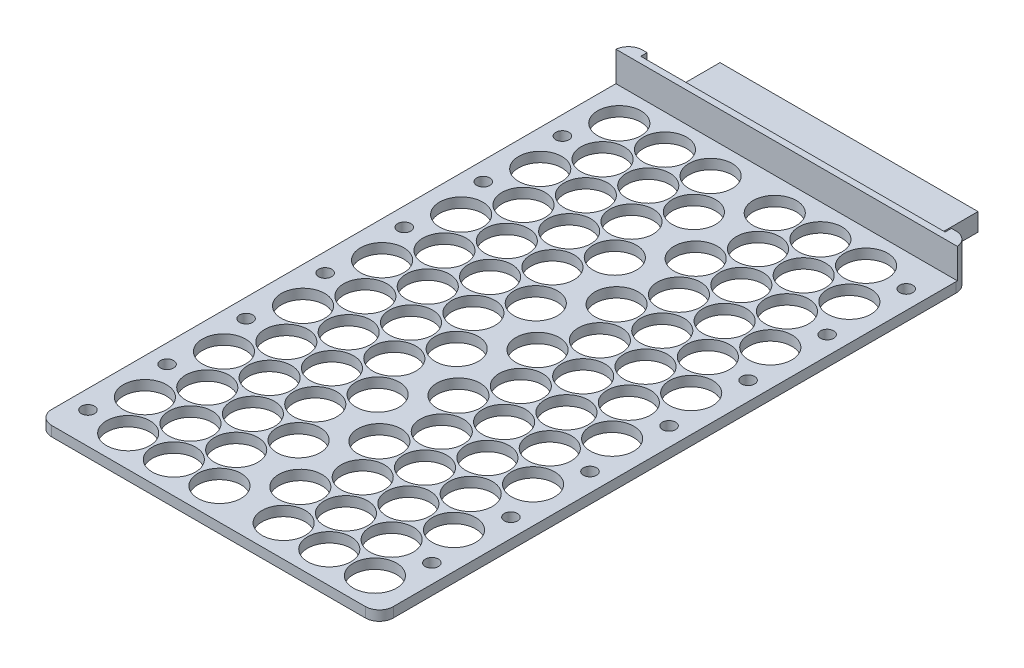
SolidWorks part; units mm, degrees
ref_plane "Front Plane" through (0, 0, 0) normal (0, 0, 1) x (1, 0, 0)
ref_plane "Top Plane" through (0, 0, 0) normal (0, 1, 0) x (1, 0, 0)
ref_plane "Right Plane" through (0, 0, 0) normal (1, 0, 0) x (0, 0, -1)
sketch "Sketch2" plane through (0, 0, 0) normal (0, 1, 0) x (1, 0, 0)
  line L1 (0, 0) -> (171.7, 0)
  line L2 (0, 0) -> (0, 290.6287)
  line L3 (0, 290.6287) -> (171.7, 290.6287)
  line L4 (171.7, 0) -> (171.7, 290.6287)
  dimension "D1" = 171.7
  dimension "D2" = 290.6287
extrude "Boss-Extrude6" add sketch "Sketch2" along normal blind 5
sketch "Sketch1" plane through (0, 0, 0) normal (0, 1, 0) x (1, 0, 0)
  line L1 (0, 0) -> (171.7029, 0)
  line L2 (0, 0) -> (0, 290.6287)
  line L3 (0, 290.6287) -> (171.7029, 290.6287)
  line L4 (171.7029, 0) -> (171.7029, 290.6287)
  line L5 (29.5647, 15.875) -> (18.0897, 35.7503) construction
  line L6 (18.0897, 35.7503) -> (18.0897, 15.875) construction
  line L7 (18.0897, 15.875) -> (29.5647, 15.875) construction
  line L8 (29.5647, 55.6256) -> (18.0897, 35.7503) construction
  line L9 (18.0897, 35.7503) -> (29.5647, 35.7503) construction
  line L10 (29.5647, 35.7503) -> (29.5647, 55.6256) construction
  line L11 (29.5647, 55.6256) -> (0, 55.6256) construction
  line L12 (0, 55.6256) -> (18.0897, 75.5008) construction
  line L13 (142.1382, 35.7503) -> (171.7029, 35.7503) construction
  line L14 (171.7029, 35.7503) -> (153.6132, 15.875) construction
  circle A1 centre (29.5647, 15.875) radius 10.875
  circle A2 centre (18.0897, 35.7503) radius 10.875
  circle A3 centre (41.0397, 35.7503) radius 10.875
  circle A4 centre (52.5147, 15.875) radius 10.875
  circle A5 centre (63.9897, 35.7503) radius 10.875
  circle A6 centre (75.4647, 15.875) radius 10.875
  circle A43 centre (96.2382, 35.7503) radius 10.875
  circle A44 centre (119.1882, 35.7503) radius 10.875
  circle A45 centre (142.1382, 35.7503) radius 10.875
  circle A46 centre (153.6132, 15.875) radius 10.875
  circle A47 centre (130.6632, 15.875) radius 10.875
  circle A48 centre (107.7132, 15.875) radius 10.875
  circle A49 centre (96.2382, 75.5008) radius 10.875
  circle A50 centre (119.1882, 75.5008) radius 10.875
  circle A51 centre (142.1382, 75.5008) radius 10.875
  circle A52 centre (153.6132, 55.6256) radius 10.875
  circle A53 centre (130.6632, 55.6256) radius 10.875
  circle A54 centre (107.7132, 55.6256) radius 10.875
  circle A55 centre (96.2382, 115.2514) radius 10.875
  circle A56 centre (119.1882, 115.2514) radius 10.875
  circle A57 centre (142.1382, 115.2514) radius 10.875
  circle A58 centre (153.6132, 95.3761) radius 10.875
  circle A59 centre (130.6632, 95.3761) radius 10.875
  circle A60 centre (107.7132, 95.3761) radius 10.875
  circle A61 centre (96.2382, 155.002) radius 10.875
  circle A62 centre (119.1882, 155.002) radius 10.875
  circle A63 centre (142.1382, 155.002) radius 10.875
  circle A64 centre (153.6132, 135.1267) radius 10.875
  circle A65 centre (130.6632, 135.1267) radius 10.875
  circle A66 centre (107.7132, 135.1267) radius 10.875
  circle A67 centre (96.2382, 194.7525) radius 10.875
  circle A68 centre (119.1882, 194.7525) radius 10.875
  circle A69 centre (142.1382, 194.7525) radius 10.875
  circle A70 centre (153.6132, 174.8773) radius 10.875
  circle A71 centre (130.6632, 174.8773) radius 10.875
  circle A72 centre (107.7132, 174.8773) radius 10.875
  circle A73 centre (96.2382, 234.5031) radius 10.875
  circle A74 centre (119.1882, 234.5031) radius 10.875
  circle A75 centre (142.1382, 234.5031) radius 10.875
  circle A76 centre (153.6132, 214.6278) radius 10.875
  circle A77 centre (130.6632, 214.6278) radius 10.875
  circle A78 centre (107.7132, 214.6278) radius 10.875
  circle A79 centre (96.2382, 274.2537) radius 10.875
  circle A80 centre (119.1882, 274.2537) radius 10.875
  circle A81 centre (142.1382, 274.2537) radius 10.875
  circle A82 centre (153.6132, 254.3784) radius 10.875
  circle A83 centre (130.6632, 254.3784) radius 10.875
  circle A84 centre (107.7132, 254.3784) radius 10.875
  circle A127 centre (18.0897, 75.5008) radius 10.875
  circle A128 centre (41.0397, 75.5008) radius 10.875
  circle A129 centre (63.9897, 75.5008) radius 10.875
  circle A130 centre (75.4647, 55.6256) radius 10.875
  circle A131 centre (52.5147, 55.6256) radius 10.875
  circle A132 centre (29.5647, 55.6256) radius 10.875
  circle A133 centre (18.0897, 115.2514) radius 10.875
  circle A134 centre (41.0397, 115.2514) radius 10.875
  circle A135 centre (63.9897, 115.2514) radius 10.875
  circle A136 centre (75.4647, 95.3761) radius 10.875
  circle A137 centre (52.5147, 95.3761) radius 10.875
  circle A138 centre (29.5647, 95.3761) radius 10.875
  circle A139 centre (18.0897, 155.002) radius 10.875
  circle A140 centre (41.0397, 155.002) radius 10.875
  circle A141 centre (63.9897, 155.002) radius 10.875
  circle A142 centre (75.4647, 135.1267) radius 10.875
  circle A143 centre (52.5147, 135.1267) radius 10.875
  circle A144 centre (29.5647, 135.1267) radius 10.875
  circle A145 centre (18.0897, 194.7525) radius 10.875
  circle A146 centre (41.0397, 194.7525) radius 10.875
  circle A147 centre (63.9897, 194.7525) radius 10.875
  circle A148 centre (75.4647, 174.8773) radius 10.875
  circle A149 centre (52.5147, 174.8773) radius 10.875
  circle A150 centre (29.5647, 174.8773) radius 10.875
  circle A151 centre (18.0897, 234.5031) radius 10.875
  circle A152 centre (41.0397, 234.5031) radius 10.875
  circle A153 centre (63.9897, 234.5031) radius 10.875
  circle A154 centre (75.4647, 214.6278) radius 10.875
  circle A155 centre (52.5147, 214.6278) radius 10.875
  circle A156 centre (29.5647, 214.6278) radius 10.875
  circle A157 centre (18.0897, 274.2537) radius 10.875
  circle A158 centre (41.0397, 274.2537) radius 10.875
  circle A159 centre (63.9897, 274.2537) radius 10.875
  circle A160 centre (75.4647, 254.3784) radius 10.875
  circle A161 centre (52.5147, 254.3784) radius 10.875
  circle A162 centre (29.5647, 254.3784) radius 10.875
  point P10 (0, 0)
  dimension "D1" = 21.75
  dimension "D2" = 15.875
  dimension "D3" = 22.95
  dimension "D5" = 60
  dimension "D8" = 22.95
  dimension "D9" = 22.95
  dimension "D10" = 60
  dimension "D13" = 28.75
  dimension "D4" = 16.375
  dimension "D16" = 26.875
  dimension "D14" = 26.875
  dimension "D6" = 3
  dimension "D7" = 1
  dimension "D11" = 2
  dimension "D12" = 7
extrude "Cut-Extrude1" cut sketch "Sketch1" along normal blind 7 contours A47 | A46 | A45 | A44 | A43 | A54 | A53 | A52 | A51 | A50 | A49 | A60 | A59 | A58 | A57 | A56 | A55 | A66 | A65 | A64 | A63 | A62 | A61 | A72 | A67 | A78 | A73 | A84 | A79 | A80 | A81 | A82 | A83 | A74 | A75 | A77 | A76 | A69 | A70 | A71 | A68 | A159 | A158 | A157 | A162 | A161 | A160 | A153 | A152 | A156 | A151 | A155 | A154 | A147 | A146 | A145 | A148 | A141 | A149 | A150 | A140 | A142 | A143 | A144 | A139 | A133 | A134 | A135 | A136 | A137 | A138 | A128 | A127 | A129 | A130 | A131 | A132 | A2 | A3 | A5 | A6 | A4 | A1 | A48
sketch "Sketch5" plane through (0, 5, 0) normal (0, 1, 0) x (1, 0, 0)
  line L0 (9.3449, 254.3784) -> (18.0897, 274.2537) construction
  line L1 (9.3449, 254.3784) -> (0, 254.3784) construction
  line L2 (18.0897, 234.5031) -> (9.3449, 254.3784) construction
  line L3 (18.6897, 254.3784) -> (9.3449, 254.3784) construction
  line L4 (142.1382, 75.5008) -> (162.3566, 75.5008) construction
  line L5 (0, 290.6287) -> (0, 0) construction
  line L6 (162.3566, 35.7503) -> (171.7, 35.7503) construction
  line L7 (153.6132, 15.875) -> (162.3566, 35.7503) construction
  line L8 (162.3566, 35.7503) -> (153.6132, 55.6256) construction
  line L9 (171.7, 0) -> (171.7, 290.6287) construction
  line L10 (162.3566, 35.7503) -> (153.0132, 35.7503) construction
  line L12 (29.5647, 214.6278) -> (9.3449, 214.6278) construction
  circle A1 centre (9.3449, 254.3784) radius 3.3
  circle A4 centre (162.3566, 35.7503) radius 3.3
  circle A7 centre (162.3566, 75.5008) radius 3.3
  circle A8 centre (162.3566, 115.2514) radius 3.3
  circle A9 centre (162.3566, 155.002) radius 3.3
  circle A10 centre (162.3566, 194.7525) radius 3.3
  circle A11 centre (162.3566, 234.5031) radius 3.3
  circle A12 centre (162.3566, 274.2537) radius 3.3
  circle A15 centre (9.3449, 214.6278) radius 3.3
  circle A16 centre (9.3449, 174.8773) radius 3.3
  circle A17 centre (9.3449, 135.1267) radius 3.3
  circle A18 centre (9.3449, 95.3761) radius 3.3
  circle A19 centre (9.3449, 55.6256) radius 3.3
  circle A20 centre (9.3449, 15.875) radius 3.3
  circle A21 centre (29.5647, 254.3784) radius 10.875 construction
  circle A22 centre (142.1382, 35.7503) radius 10.875 construction
  dimension "D1" = 6.6
  dimension "D2" = 6.6
  dimension "D3" = 7
  dimension "D4" = 7
extrude "Cut-Extrude3" cut sketch "Sketch5" against normal up to surface (5 mm away) up to face at (96.2382, 0, -64.6258)
sketch "Sketch12" plane through (0, 0, -290.6287) normal (0, 0, -1) x (-1, 0, 0)
  line L5 (-171.7, 5) -> (0, 5)
  line L6 (-171.7, 5) -> (-171.7, 20)
  line L7 (0, 5) -> (0, 0) construction
  line L8 (-171.7, 0) -> (0, 0)
  line L12 (-171.7, 0) -> (0, 0)
  line L13 (-171.7, 0) -> (-171.7, 5)
  line L15 (0, 0) -> (0, 5)
  line L16 (-171.7, 20) -> (0, 20)
  line L17 (-171.7, 5) -> (0, 5)
  line L26 (-171.7, 5) -> (0, 5) construction
  line L27 (0, 5) -> (0, 20)
  dimension "D1" = 15
extrude "Boss-Extrude9" add sketch "Sketch12" along normal blind 6.35
sketch "Sketch13" plane through (0, 0, -296.9787) normal (0, 0, -1) x (-1, 0, 0)
  line L1 (-162.355, 9) -> (-9.345, 9)
  line L2 (-162.355, 9) -> (-162.355, 20)
  line L3 (-162.355, 20) -> (-9.345, 20)
  line L4 (-9.345, 9) -> (-9.345, 20)
  line L8 (-162.355, 20) -> (-171.7, 20) construction
  line L10 (-171.7, 20) -> (0, 20) construction
  line L11 (-9.345, 20) -> (0, 20) construction
  dimension "D1" = 153.01
  dimension "D2" = 11
extrude "Cut-Extrude7" cut sketch "Sketch13" against normal blind 3.18
sketch "Sketch14" plane through (0, 0, -296.9787) normal (0, 0, -1) x (-1, 0, 0)
  line L6 (-171.7, 20) -> (-171.7, 0) construction
  line L7 (0, 0) -> (0, 20) construction
  line L9 (-150.7, 0) -> (-21, 0)
  line L10 (-150.7, 0) -> (-150.7, 9)
  line L11 (-150.7, 9) -> (-21, 9)
  line L12 (-21, 0) -> (-21, 9)
  line L14 (-150.7, 0) -> (-171.7, 0) construction
  line L15 (-171.7, 0) -> (0, 0) construction
  line L16 (-21, 0) -> (0, 0) construction
  line L17 (-162.355, 9) -> (-9.345, 9) construction
  point P8 (0, 0)
  point P13 (0, 0)
  point P16 (0, 0)
  dimension "D1" = 21
extrude "Boss-Extrude10" add sketch "Sketch14" along normal blind 25
fillet "Fillet1" radius 7 8 edges at (171.7, 12.5, -290.6287) (171.7, 20, -293.8037) (0, 12.5, -290.6287) (0, 20, -293.8037) (171.7, 10, -296.9787) (0, 10, -296.9787) (171.7, 2.5, 0) (0, 2.5, 0)
equation "\"cellDia\"= 21.55mm"
equation "\"cellRad\"= \"cellDia\" / 2"
equation "\"cellGap\"= 1.2mm"
equation "\"holeTol\"= .1mm"
equation "\"holeDia\"= \"cellDia\" + 2 * \"holeTol\""
equation "\"cellAngle\"= 30deg"
equation "\"groupWidth\" = \"longRailGap\" + 4 * ( \"holeDia\" + \"cellGap\" ) + \"shortRailGap\" + \"middleGapStraight\" + 2 * \"holeDia\""
equation "\"groupHeight\" = 13 * ( \"holeDia\" + \"cellGap\" ) * cos ( \"cellAngle\" ) + \"holeDia\" + \"topEdge\" + \"bottomEdge\""
equation "\"senseSpace\"= 5mm"
equation "\"outEdge\"= 0mm"
equation "\"topEdge\"= 5.5mm"
equation "\"bottomEdge\"= 5mm"
equation "\"blockWidth\"= ( 2 * \"outEdge\" ) + ( 2 * \"groupWidth\" ) + \"senseSpace\""
equation "\"blockHeight\"= \"topEdge\" + \"bottomEdge\" + \"groupHeight\" + \"BMSSpace\""
equation "\"cellLinSpace\"= \"holeDia\" + \"cellGap\""
equation "\"standThickness\" = 6"
equation "\"blockThickness\"=5"
equation "\"railThickness\"= \"blockThickness\" + \"standThickness\""
equation "\"railWidth\"= 16mm"
equation "\"boltSpacing\"= 42mm"
equation "\"nippleDia\"= 7mm"
equation "\"senseWidth\"=15.9635"
equation "\"senseHeight\"=10"
equation "\"railHeight\"= \"blockHeight\""
equation "\"sensePCBWidth\"=10.16"
equation "\"topTapWidth\"= 118mm"
equation "\"topTapHeight\"= 25mm"
equation "\"BMSBackPlateThickness\"= 3.175mm"
equation "\"BMSInset\"= 3.175mm"
equation "\"BMSSpace\"= \"BMSInset\" + \"BMSBackPlateThickness\""
equation "\"holeRad\"= \"holeDia\" / 2"
equation "\"BMSBackPlateHeight\"= 10mm"
equation "\"middleGap\"= 7mm"
equation "\"mountingHole\"= 10mm"
equation "\"D1@Sketch1\"=\"holeDia\""
equation "\"D3@Sketch1\"=\"holeDia\"+\"cellGap\""
equation "\"D8@Sketch1\"=\"holeDia\"+\"cellGap\""
equation "\"D9@Sketch1\"=\"holeDia\"+\"cellGap\""
equation "\"D13@Sketch1\"=\"holeDia\"+\"middleGap\""
equation "\"D16@Sketch1\"=\"holeRad\"+\"railWidth\""
equation "\"D2@Sketch1\"=\"holeRad\"+\"bottomEdge\""
equation "\"D4@Sketch1\"=\"holeRad\"+\"topEdge\""
equation "\"D14@Sketch1\"=\"holeRad\"+\"railWidth\""
equation "\"longRailGap\" = 18.69mm"
equation "\"shortRailGap\"= 7.21mm"
equation "\"middleGapStraight\"= 10.50mm"
equation "\"D2@Sketch2\"=\"groupHeight\""
equation "\"D1@Sketch2\"=\"groupWidth\""
equation "\"D1@Boss-Extrude6\"=\"blockThickness\""
equation "\"segmentBolts\"= 6.60mm"
equation "\"D1@Sketch5\"=\"segmentBolts\""
equation "\"D2@Sketch5\"=\"segmentBolts\""
equation "\"boltHead\"= 11mm"
equation "\"D1@Boss-Extrude9\"=\"BMSSpace\""
equation "\"BMSLength\"= 143mm"
equation "\"D1@Boss-Extrude10\"=\"topTapHeight\""
equation "\"D1@Cut-Extrude8\"=1"
equation "\"senseTop\"= 93.00mm"
equation "\"D2@Sketch13\"=\"BMSBackPlateHeight\"+1"
equation "\"D1@Sketch12\"=\"BMSBackPlateHeight\"+5"
equation "\"D2@Cell Block Sketch\"= \"blockHeight\""
